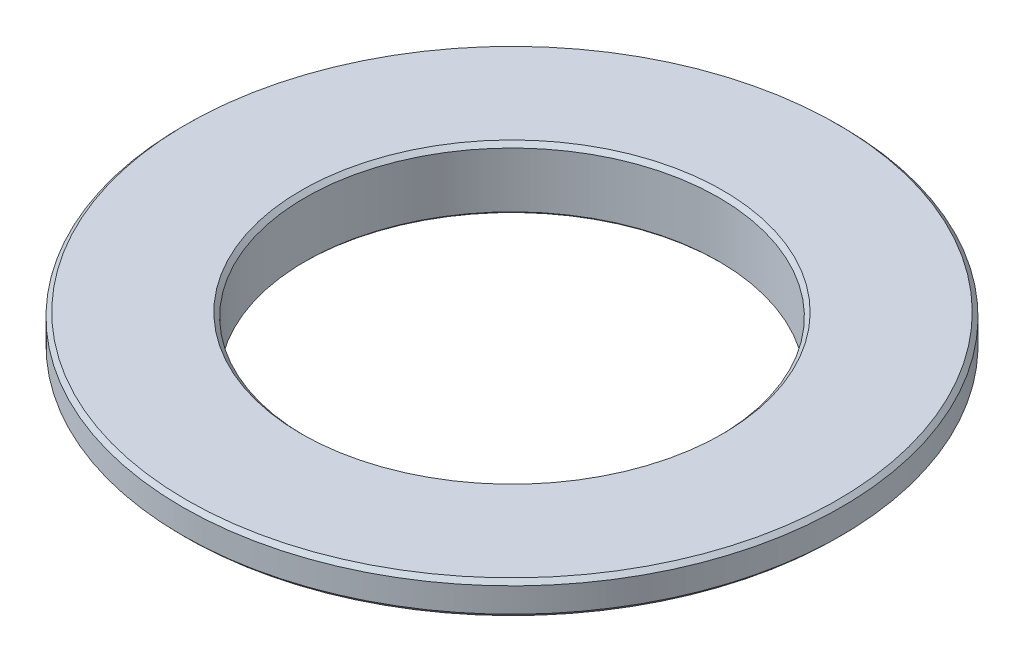
SolidWorks part; units mm, degrees
ref_plane "前基準面" through (0, 0, 0) normal (0, 0, 1) x (1, 0, 0)
ref_plane "上基準面" through (0, 0, 0) normal (0, 1, 0) x (1, 0, 0)
ref_plane "右基準面" through (0, 0, 0) normal (1, 0, 0) x (0, 0, -1)
sketch "草圖1" plane through (0, 0, 0) normal (0, 0, 1) x (1, 0, 0)
  line L0 (80.5, 19) -> (0, 19)
  line L1 (0, 19) -> (0, 11)
  line L2 (0, 11) -> (80.5, 11)
  line L3 (80.5, 11) -> (80.5, 19)
  line L4 (0, 19) -> (0, 11) construction
revolve "旋轉1" add sketch "草圖1" angle 360 about L4
sketch "草圖2" plane through (0, 11, 0) normal (0, -1, 0) x (1, 0, 0)
  circle A0 centre (0, 0) radius 65.25
extrude "填料-伸長1" add sketch "草圖2" along normal blind 7
hole_wizard "鑽孔3" positions "草圖8" profile "草圖7" legacy
sketch "草圖8" plane through (0, 4, 0) normal (0, -1, 0) x (-1, 0, 0)
  point P0 (0, 0)
sketch "草圖7" plane through (0, 4, 0) normal (1, 0, 0) x (0, 0, -1)
  line L0 (0, 0) -> (0, 15)
  line L1 (0, 15) -> (50.5, 15)
  line L2 (50.5, 15) -> (50.5, 0)
  line L3 (50.5, 0) -> (0, 0)
  line L4 (0, 110) -> (0, -10) construction
  dimension "直徑" = 101
  dimension "深度" = 15
chamfer "導角1" distance 0.5 angle 45 2 edges at (0, 4, -65.25) (0, 4, -50.5)
chamfer "導角2" distance 1 angle 45 3 edges at (0, 19, -80.5) (0, 11, -80.5) (0, 19, -50.5)
